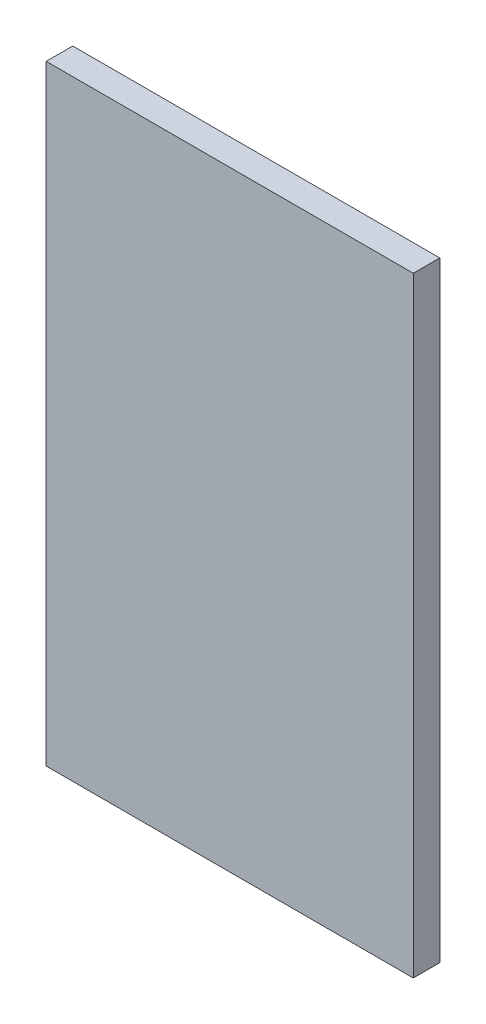
SolidWorks part; units mm, degrees
material "Pine"
ref_plane "Front Plane" through (0, 0, 0) normal (0, 0, 1) x (1, 0, 0)
ref_plane "Top Plane" through (0, 0, 0) normal (0, 1, 0) x (1, 0, 0)
ref_plane "Right Plane" through (0, 0, 0) normal (1, 0, 0) x (0, 0, -1)
sketch "Sketch3" plane through (0, 0, 0) normal (0, 0, 1) x (1, 0, 0)
  line L4 (417, 206) -> (583, 206)
  line L5 (417, 206) -> (417, -70)
  line L6 (417, -70) -> (583, -70)
  line L7 (583, 206) -> (583, -70)
  line L8 (417, 206) -> (583, -70) construction
  line L9 (417, -70) -> (583, 206) construction
  point P6 (500, 68)
  dimension "D1" = 166
  dimension "D2" = 276
extrude "Boss-Extrude2" add sketch "Sketch3" along normal blind 12 separate body
sketch "Sketch4" [suppressed] plane through (0, 0, 12) normal (0, 0, 1) x (1, 0, 0)
  line L1 (442.6085, 191.5854) -> (556.8131, 191.5854)
  line L2 (432.6085, 181.5854) -> (432.6085, 99.4004)
  line L3 (442.6085, 89.4004) -> (556.8131, 89.4004)
  line L4 (566.8131, 181.5854) -> (566.8131, 99.4004)
  line L5 (432.6085, 191.5854) -> (566.8131, 89.4004) construction
  line L6 (432.6085, 89.4004) -> (566.8131, 191.5854) construction
  line L7 (438.5839, 77.616) -> (560.5839, 77.616) construction
  line L8 (438.5839, 77.616) -> (438.5839, -46.384) construction
  line L9 (438.5839, -46.384) -> (560.5839, -46.384) construction
  line L10 (560.5839, 77.616) -> (560.5839, -46.384) construction
  line L11 (213.067, 66.7937) -> (345.067, 66.7937) construction
  line L12 (213.067, 66.7937) -> (213.067, -0.2063) construction
  line L13 (213.067, -0.2063) -> (345.067, -0.2063) construction
  line L14 (345.067, 66.7937) -> (345.067, -0.2063) construction
  line L15 (465.4441, 183.8582) -> (567.4441, 183.8582)
  line L16 (465.4441, 183.8582) -> (465.4441, 98.8582)
  line L17 (465.4441, 98.8582) -> (567.4441, 98.8582)
  line L18 (567.4441, 183.8582) -> (567.4441, 98.8582)
  arc A0 (432.6085, 99.4004) -> (442.6085, 89.4004) centre (442.6085, 99.4004) ccw
  arc A1 (556.8131, 89.4004) -> (566.8131, 99.4004) centre (556.8131, 99.4004) ccw
  arc A2 (556.8131, 191.5854) -> (566.8131, 181.5854) centre (556.8131, 181.5854) cw
  arc A3 (442.6085, 191.5854) -> (432.6085, 181.5854) centre (442.6085, 181.5854) ccw
  point P0 (499.7108, 140.4929)
  dimension "D1" = 10
equation "\"LENGTH\" = 1000mm"
equation "\"PLY\"= 12mm"
equation "\"CENTER_BRACE_LENGTH\" = 393mm"
equation "\"PANEL_WIDTH\"= \"LENGTH\" - \"CENTER_BRACE_LENGTH\" * 2 - \"PLY\" * 4"
equation "\"D1@Boss-Extrude2\"=\"PLY\""
equation "\"D1@Sketch3\"=\"PANEL_WIDTH\""
equation "\"PANEL_SMALL_HEIGHT\" = 70mm"
equation "\"D2@Sketch3\"=\"WIDTH\" - \"PLY\" * 2"
equation "\"WIDTH\" = 300mm"
